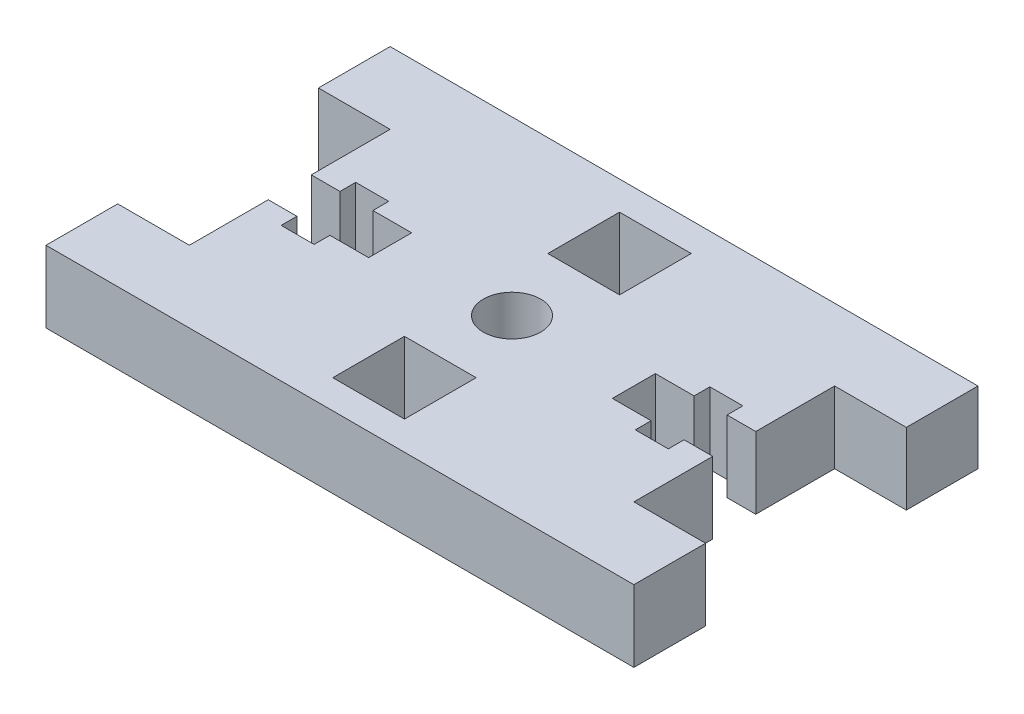
SolidWorks part; units mm, degrees
ref_plane "Front Plane" through (0, 0, 0) normal (0, 0, 1) x (1, 0, 0)
ref_plane "Top Plane" through (0, 0, 0) normal (0, 1, 0) x (1, 0, 0)
ref_plane "Right Plane" through (0, 0, 0) normal (1, 0, 0) x (0, 0, -1)
sketch "Sketch1" plane through (0, 0, 0) normal (0, 1, 0) x (1, 0, 0)
  line L0 (51.3755, 21.289) -> (44.3755, 18.289) construction
  line L1 (44.3755, 7.789) -> (75.3755, 7.789)
  line L2 (44.3755, 31.789) -> (75.3755, 31.789)
  line L3 (75.3755, 12.789) -> (75.3755, 18.289)
  line L4 (59.8755, 31.789) -> (59.8755, 7.789) construction
  line L5 (51.3755, 18.289) -> (44.3755, 21.289) construction
  line L6 (44.3755, 7.789) -> (39.3755, 7.789)
  line L7 (39.3755, 7.789) -> (39.3755, 12.789)
  line L8 (44.3755, 12.789) -> (44.3755, 18.289)
  line L9 (71.0755, 17.189) -> (73.3755, 17.189)
  line L10 (68.3755, 18.289) -> (71.0755, 18.289)
  line L11 (68.3755, 18.289) -> (68.3755, 21.289)
  line L12 (68.3755, 21.289) -> (71.0755, 21.289)
  line L13 (68.3755, 18.289) -> (75.3755, 21.289) construction
  line L14 (68.3755, 21.289) -> (75.3755, 18.289) construction
  line L15 (71.0755, 21.289) -> (71.0755, 22.389)
  line L16 (71.0755, 22.389) -> (73.3755, 22.389)
  line L17 (73.3755, 21.289) -> (73.3755, 22.389)
  line L18 (73.3755, 18.289) -> (73.3755, 17.189)
  line L19 (71.0755, 18.289) -> (71.0755, 17.189)
  line L20 (73.3755, 21.289) -> (75.3755, 21.289)
  line L21 (73.3755, 18.289) -> (75.3755, 18.289)
  line L22 (75.3755, 21.289) -> (75.3755, 26.789)
  line L23 (75.3755, 12.789) -> (80.3755, 12.789)
  line L24 (75.3755, 31.789) -> (80.3755, 31.789)
  line L25 (75.3755, 26.789) -> (80.3755, 26.789)
  line L26 (80.3755, 31.789) -> (80.3755, 26.789)
  line L27 (80.3755, 7.789) -> (80.3755, 12.789)
  line L28 (75.3755, 7.789) -> (80.3755, 7.789)
  line L29 (39.3755, 31.789) -> (39.3755, 26.789)
  line L30 (44.3755, 26.789) -> (39.3755, 26.789)
  line L31 (44.3755, 31.789) -> (39.3755, 31.789)
  line L32 (44.3755, 12.789) -> (39.3755, 12.789)
  line L33 (44.3755, 21.289) -> (44.3755, 26.789)
  line L34 (46.3755, 18.289) -> (44.3755, 18.289)
  line L35 (46.3755, 21.289) -> (44.3755, 21.289)
  line L36 (48.6755, 18.289) -> (48.6755, 17.189)
  line L37 (46.3755, 18.289) -> (46.3755, 17.189)
  line L38 (46.3755, 21.289) -> (46.3755, 22.389)
  line L39 (48.6755, 22.389) -> (46.3755, 22.389)
  line L40 (48.6755, 21.289) -> (48.6755, 22.389)
  line L41 (51.3755, 21.289) -> (48.6755, 21.289)
  line L42 (51.3755, 18.289) -> (51.3755, 21.289)
  line L43 (51.3755, 18.289) -> (48.6755, 18.289)
  line L44 (48.6755, 17.189) -> (46.3755, 17.189)
  line L45 (68.3755, 19.789) -> (59.8755, 19.789) construction
  point P23 (47.8755, 19.789)
  point P25 (71.8755, 19.789)
  point P44 (59.8755, 19.789)
  dimension "D2" = 31
  dimension "D3" = 3
  dimension "D4" = 5
  dimension "D5" = 5
  dimension "D6" = 2
  dimension "D7" = 2.3
  dimension "D8" = 2.7
  dimension "D9" = 1.1
  dimension "D10" = 5
  dimension "D11" = 24
extrude "Boss-Extrude1" add sketch "Sketch1" along normal blind 5
sketch "Sketch2" plane through (0, 5, 0) normal (0, 1, 0) x (1, 0, 0)
  line L0 (59.8755, 31.789) -> (59.8755, 7.789) construction
  line L1 (80.3755, 31.789) -> (39.3755, 31.789) construction
  line L2 (39.3755, 7.789) -> (80.3755, 7.789) construction
  line L3 (51.3755, 19.789) -> (59.8755, 19.789) construction
  line L4 (51.3755, 21.289) -> (51.3755, 18.289) construction
  line L5 (57.3755, 9.789) -> (62.3755, 9.789)
  line L6 (57.3755, 24.789) -> (62.3755, 24.789)
  line L7 (57.3755, 24.789) -> (57.3755, 29.789)
  line L8 (57.3755, 29.789) -> (62.3755, 29.789)
  line L9 (62.3755, 24.789) -> (62.3755, 29.789)
  line L10 (57.3755, 24.789) -> (62.3755, 29.789) construction
  line L11 (57.3755, 29.789) -> (62.3755, 24.789) construction
  line L12 (62.3755, 14.789) -> (62.3755, 9.789)
  line L13 (57.3755, 14.789) -> (62.3755, 14.789)
  line L14 (57.3755, 14.789) -> (57.3755, 9.789)
  circle A0 centre (59.8755, 19.789) radius 2
  point P10 (59.8755, 27.289)
  dimension "D3" = 4
  dimension "D1" = 5
  dimension "D2" = 5
  dimension "D4" = 2
extrude "Cut-Extrude1" cut sketch "Sketch2" against normal blind 10
